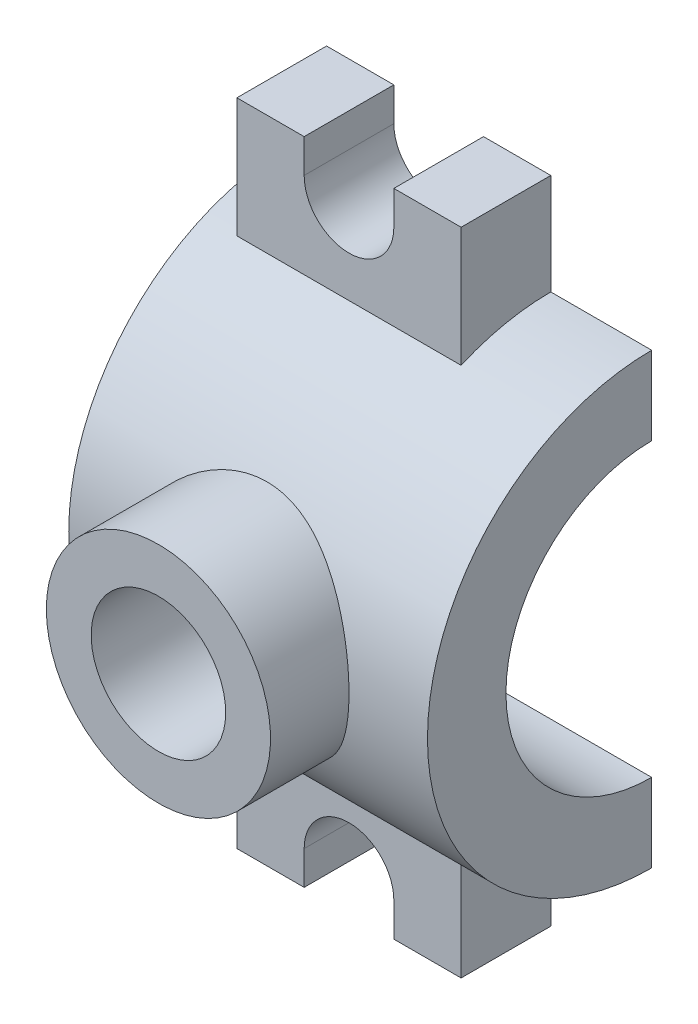
SolidWorks part; units mm, degrees
ref_plane "前视基准面" through (0, 0, 0) normal (0, 0, 1) x (1, 0, 0)
ref_plane "上视基准面" through (0, 0, 0) normal (0, 1, 0) x (1, 0, 0)
ref_plane "右视基准面" through (0, 0, 0) normal (1, 0, 0) x (0, 0, -1)
sketch "草图1" plane through (0, 0, 0) normal (1, 0, 0) x (0, 0, -1)
  line L2 (0, 20) -> (0, -20)
  arc A0 (0, 20) -> (0, -20) centre (0, 0) ccw
  dimension "D1" = 20
extrude "凸台-拉伸1" add sketch "草图1" along normal blind 32
sketch "草图2" plane through (0, 0, 0) normal (0, 0, -1) x (-1, 0, 0)
  circle A0 centre (-15, 0) radius 10
  dimension "D1" = 20
  dimension "D2" = 15
extrude "凸台-拉伸2" add sketch "草图2" against normal blind 27
sketch "草图3" plane through (0, 0, 0) normal (0, 0, -1) x (-1, 0, 0)
  line L5 (-3, -29) -> (-23, -29)
  line L6 (-3, -29) -> (-3, 29)
  line L8 (-3, 29) -> (-23, 29)
  line L9 (-23, -29) -> (-23, 29)
  line L14 (-3, -29) -> (-23, 29) construction
  line L15 (-3, 29) -> (-23, -29) construction
  point P0 (-13, 0)
  dimension "D1" = 58
  dimension "D2" = 13
  dimension "D3" = 20
extrude "凸台-拉伸3" add sketch "草图3" against normal blind 8
sketch "草图4" plane through (0, 0, 27) normal (0, 0, 1) x (1, 0, 0)
  circle A0 centre (15, 0) radius 6
  dimension "D1" = 12
extrude "切除-拉伸1" cut sketch "草图4" against normal through all
sketch "草图5" plane through (32, 0, 0) normal (1, 0, 0) x (0, 0, -1)
  line L0 (0, 13) -> (0, -13)
  arc A0 (0, 13) -> (0, -13) centre (0, 0) ccw
  dimension "D1" = 26
extrude "切除-拉伸2" cut sketch "草图5" against normal through all
sketch "草图6" plane through (0, 0, 0) normal (0, 0, -1) x (-1, 0, 0)
  line L0 (-17, 26) -> (-17, 29)
  line L1 (-3, 29) -> (-23, 29) construction
  line L2 (-17, 29) -> (-9, 29)
  line L3 (-9, 29) -> (-9, 26)
  line L4 (0, 13) -> (0, 20) construction
  line L5 (0, 0) -> (-26.5636, 0) construction
  line L6 (-17, -26) -> (-17, -29)
  line L7 (-17, -29) -> (-9, -29)
  line L8 (-9, -29) -> (-9, -26)
  arc A0 (-17, 26) -> (-9, 26) centre (-13, 26) ccw
  arc A1 (-17, -26) -> (-9, -26) centre (-13, -26) cw
  dimension "D3" = 4
  dimension "D1" = 13
  dimension "D2" = 52
extrude "切除-拉伸4" cut sketch "草图6" against normal blind 8
